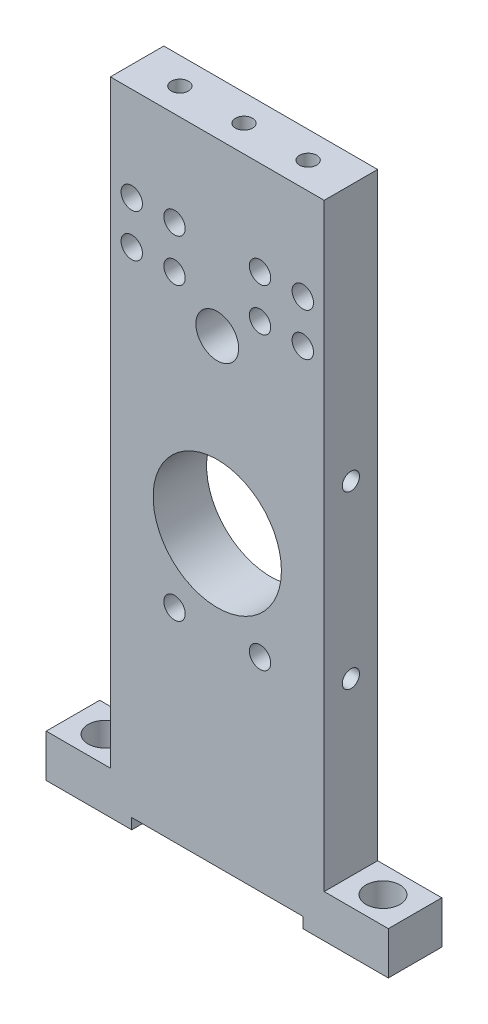
SolidWorks part; units mm, degrees
material "6061 Alloy"
ref_plane "Front Plane" through (0, 0, 0) normal (0, 0, 1) x (1, 0, 0)
ref_plane "Top Plane" through (0, 0, 0) normal (0, 1, 0) x (1, 0, 0)
ref_plane "Right Plane" through (0, 0, 0) normal (1, 0, 0) x (0, 0, -1)
sketch "Sketch1" plane through (0, 0, 0) normal (0, 1, 0) x (1, 0, 0)
  line L1 (-50.8, 7.9375) -> (50.8, 7.9375)
  line L2 (-50.8, 7.9375) -> (-50.8, -7.9375)
  line L3 (-50.8, -7.9375) -> (50.8, -7.9375)
  line L4 (50.8, 7.9375) -> (50.8, -7.9375)
  dimension "D1" = 7.9375
  dimension "D2" = 7.9375
  dimension "D3" = 50.8
  dimension "D4" = 50.8
extrude "Boss-Extrude1" add sketch "Sketch1" along normal blind 190.5
sketch "Sketch2" plane through (0, 0, 7.9375) normal (0, 0, 1) x (1, 0, 0)
  line L0 (-50.8, 0) -> (50.8, 0) construction
  line L1 (-50.8, 190.5) -> (-31.75, 190.5)
  line L2 (-50.8, 190.5) -> (-50.8, 12.7)
  line L3 (-50.8, 12.7) -> (-31.75, 12.7)
  line L4 (-31.75, 190.5) -> (-31.75, 12.7)
  line L5 (50.8, 190.5) -> (31.75, 190.5)
  line L6 (50.8, 190.5) -> (50.8, 12.7)
  line L7 (50.8, 12.7) -> (31.75, 12.7)
  line L8 (31.75, 190.5) -> (31.75, 12.7)
  dimension "D1" = 19.05
  dimension "D2" = 19.05
  dimension "D3" = 12.7
  dimension "D4" = 12.7
extrude "Cut-Extrude1" cut sketch "Sketch2" against normal up to next
sketch "Sketch4" plane through (0, 0, 7.9375) normal (0, 0, 1) x (1, 0, 0)
  line L0 (-50.8, 0) -> (50.8, 0) construction
  line L1 (-25.4, 0) -> (25.4, 0)
  line L2 (-25.4, 0) -> (-25.4, 3.175)
  line L3 (-25.4, 3.175) -> (25.4, 3.175)
  line L4 (25.4, 0) -> (25.4, 3.175)
  line L5 (-50.8, 12.7) -> (-50.8, 0) construction
  line L6 (50.8, 12.7) -> (50.8, 0) construction
  dimension "D1" = 25.4
  dimension "D2" = 25.4
  dimension "D3" = 3.175
extrude "Cut-Extrude2" cut sketch "Sketch4" against normal up to next
hole_wizard "3/8 Clearance Hole1" positions "Sketch8" profile "Sketch7" hole size "3/8" standard "ANSI Inch"
sketch "Sketch8" plane through (0, 12.7, 0) normal (0, 1, 0) x (-1, 0, 0)
  line L0 (-50.8, -7.9375) -> (-50.8, 7.9375) construction
  line L1 (50.8, -7.9375) -> (50.8, 7.9375) construction
  point P0 (41.275, 0)
  point P2 (-41.275, 0)
  dimension "D1" = 9.525
  dimension "D2" = 9.525
sketch "Sketch7" plane through (-41.275, 12.7, 0) normal (1, 0, 0) x (0, 0, 1)
  line L0 (0, 0) -> (0, 41.6375)
  line L1 (0, 41.6375) -> (5.0419, 38.608)
  line L2 (5.0419, 38.608) -> (5.0419, 0)
  line L5 (5.0419, 0) -> (0, 0)
  line L10 (0, 41.6375) -> (-5.0419, 38.608) construction
  line L11 (0, -6.35) -> (0, 107.95) construction
  dimension "Hole Dia." = 10.0838
  dimension "Hole Depth" = 38.608
  dimension "Drill Angle" = 118
hole_wizard "1/4 (0.25) Diameter Hole2" positions "Sketch10" profile "Sketch9" hole size "1/4" standard "ANSI Inch" end condition up to next
sketch "Sketch10" plane through (0, 0, 7.9375) normal (0, 0, 1) x (1, 0, 0)
  line L1 (25.4, 0) -> (50.8, 0) construction
  point P4 (12.7, 149.86)
  point P6 (25.4, 149.86)
  dimension "D2" = 149.86
  dimension "D3" = 12.7
  dimension "D4" = 12.7
sketch "Sketch9" plane through (12.7, 149.86, 7.9375) normal (1, 0, 0) x (0, -1, 0)
  line L0 (0, 0) -> (0, 15.876)
  line L1 (0, 15.876) -> (3.175, 15.876)
  line L2 (3.175, 15.876) -> (3.175, 0)
  line L5 (3.175, 0) -> (0, 0)
  line L11 (0, -6.35) -> (0, 107.95) construction
  dimension "Thru Hole Dia." = 6.35
  dimension "Thru Hole Depth" = 15.876
sketch "Sketch11" plane through (0, 0, 7.9375) normal (0, 0, 1) x (1, 0, 0)
  circle A0 centre (0, 88.9) radius 19.05
  dimension "D1" = 88.9
  dimension "D2" = 38.1
extrude "Cut-Extrude3" cut sketch "Sketch11" against normal up to next
hole_wizard "1/4-20 Tapped Hole2" positions "Sketch13" profile "Sketch12" tap size "1/4-20" standard "ANSI Inch"
sketch "Sketch13" plane through (0, 190.5, 0) normal (0, 1, 0) x (1, 0, 0)
  point P0 (-19.05, 0)
  point P2 (19.05, 0)
  point P6 (0, 0)
  dimension "D1" = 19.05
  dimension "D2" = 19.05
sketch "Sketch12" plane through (-19.05, 190.5, 0) normal (1, 0, 0) x (0, 0, 1)
  line L0 (0, 0) -> (0, 20.0758)
  line L1 (0, 20.0758) -> (2.5527, 18.542)
  line L2 (2.5527, 18.542) -> (2.5527, 0)
  line L5 (2.5527, 0) -> (0, 0)
  line L10 (0, 20.0758) -> (-2.5527, 18.542) construction
  line L11 (0, -6.35) -> (0, 107.95) construction
  dimension "Tap Drill Dia." = 5.1054
  dimension "Tap Drill Depth" = 18.542
  dimension "Drill Angle" = 118
cosmetic thread "Hole Thread5" parameters "D1"=12.192, "D2"=6.35
cosmetic thread "Hole Thread6" parameters "D1"=12.192, "D2"=6.35
cosmetic thread "Hole Thread7" parameters "D1"=12.192, "D2"=6.35
pattern_linear "LPattern1" count 2 spacing 12.7 along (0, 1, 0) of "1/4 (0.25) Diameter Hole2"
hole_wizard "1/4 (0.25) Diameter Hole1" positions "Sketch15" profile "Sketch14" hole size "1/4" standard "ANSI Inch"
sketch "Sketch15" plane through (0, 0, 7.9375) normal (0, 0, 1) x (1, 0, 0)
  point P0 (-12.7, 63.5)
  point P2 (12.7, 63.5)
  dimension "D1" = 12.7
  dimension "D2" = 12.7
  dimension "D3" = 63.5
sketch "Sketch14" plane through (-12.7, 63.5, 7.9375) normal (1, 0, 0) x (0, -1, 0)
  line L0 (0, 0) -> (0, 40.5157)
  line L1 (0, 40.5157) -> (3.175, 38.608)
  line L2 (3.175, 38.608) -> (3.175, 0)
  line L5 (3.175, 0) -> (0, 0)
  line L10 (0, 40.5157) -> (-3.175, 38.608) construction
  line L11 (0, -6.35) -> (0, 107.95) construction
  dimension "Hole Dia." = 6.35
  dimension "Hole Depth" = 38.608
  dimension "Drill Angle" = 118
hole_wizard "1/4-20 Tapped Hole3" positions "Sketch18" profile "Sketch17" tap size "1/4-20" standard "ANSI Inch"
sketch "Sketch18" plane through (31.75, 0, 0) normal (1, 0, 0) x (0, 0, -1)
  line L1 (-7.9375, 0) -> (7.9375, 0) construction
  point P4 (0, 114.3)
  point P10 (0, 63.5)
  dimension "D4" = 63.5
sketch "Sketch17" plane through (31.75, 114.3, 0) normal (0, 1, 0) x (0, 0, -1)
  line L0 (0, 0) -> (0, 20.0758)
  line L1 (0, 20.0758) -> (2.5527, 18.542)
  line L2 (2.5527, 18.542) -> (2.5527, 0)
  line L5 (2.5527, 0) -> (0, 0)
  line L10 (0, 20.0758) -> (-2.5527, 18.542) construction
  line L11 (0, -6.35) -> (0, 107.95) construction
  dimension "Tap Drill Dia." = 5.1054
  dimension "Tap Drill Depth" = 18.542
  dimension "Drill Angle" = 118
cosmetic thread "Hole Thread8" parameters "D1"=12.192, "D2"=6.35
cosmetic thread "Hole Thread9" parameters "D1"=12.192, "D2"=6.35
mirror "Mirror2" about plane through (0, 0, 0) normal (1, 0, 0) of "1/4-20 Tapped Hole3"
sketch "Sketch19" plane through (0, 0, 7.9375) normal (0, 0, 1) x (1, 0, 0)
  line L0 (25.4, 0) -> (50.8, 0) construction
  circle A0 centre (0, 139.7) radius 6.35
  dimension "D1" = 139.7
extrude "Cut-Extrude4" cut sketch "Sketch19" against normal up to next
mirror "Mirror3" about plane through (0, 0, 0) normal (1, 0, 0) of "LPattern1", "1/4 (0.25) Diameter Hole2"
